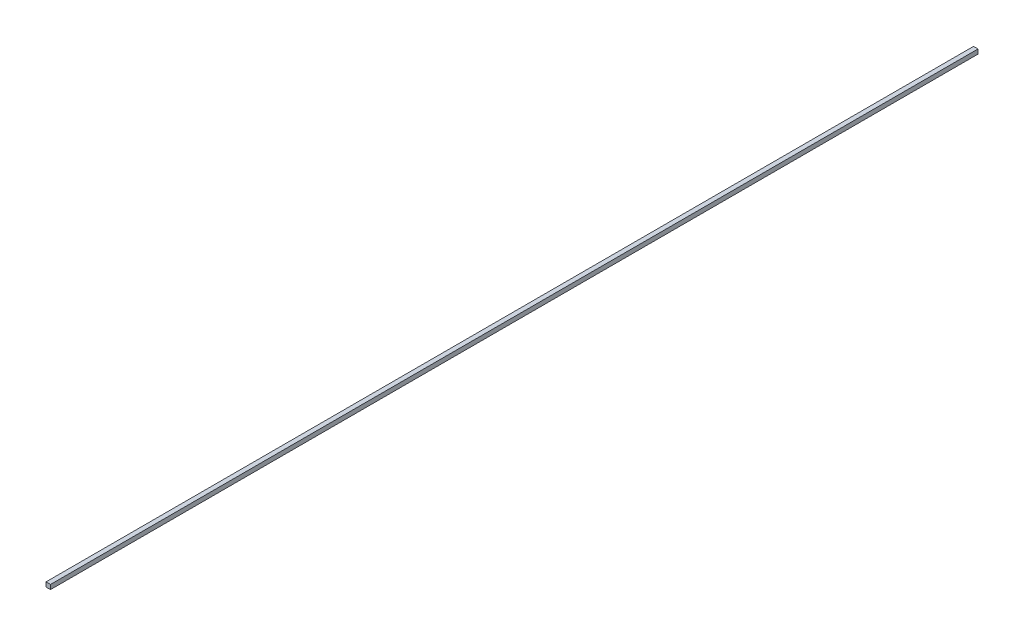
SolidWorks part; units mm, degrees
material "6061-T6 (SS)"
ref_plane "Front Plane" through (0, 0, 0) normal (0, 0, 1) x (1, 0, 0)
ref_plane "Top Plane" through (0, 0, 0) normal (0, 1, 0) x (1, 0, 0)
ref_plane "Right Plane" through (0, 0, 0) normal (1, 0, 0) x (0, 0, -1)
sketch "Sketch2" plane through (0, 0, 0) normal (0, 0, 1) x (1, 0, 0)
  line L1 (0, 0) -> (25.4, 0)
  line L2 (0, 0) -> (0, 25.4)
  line L3 (0, 25.4) -> (25.4, 25.4)
  line L4 (25.4, 0) -> (25.4, 25.4)
  dimension "D1" = 25.4
  dimension "D2" = 25.4
extrude "Boss-Extrude1" add sketch "Sketch2" along normal blind 5257.8
equation "\"b\" = 1'base of the beam"
equation "\"h\"= 1'height of the beam"
equation "\"Area\"= \"b\" * \"h\"'Cross Sectional area of [in^2]"
equation "\"F\"= 500'Load [pound force]"
equation "\"del\"= .009'max deflection[in]"
equation "\"E\"= 11500000'Youngs mod of Al [psi]"
equation "\"L\"= \"del\" * \"Area\" * \"E\" / \"F\"'Designed Length [in]"
equation "\"D1@Sketch2\"=\"h\""
equation "\"D2@Sketch2\"=\"b\""
equation "\"D1@Boss-Extrude1\"=\"L\""
